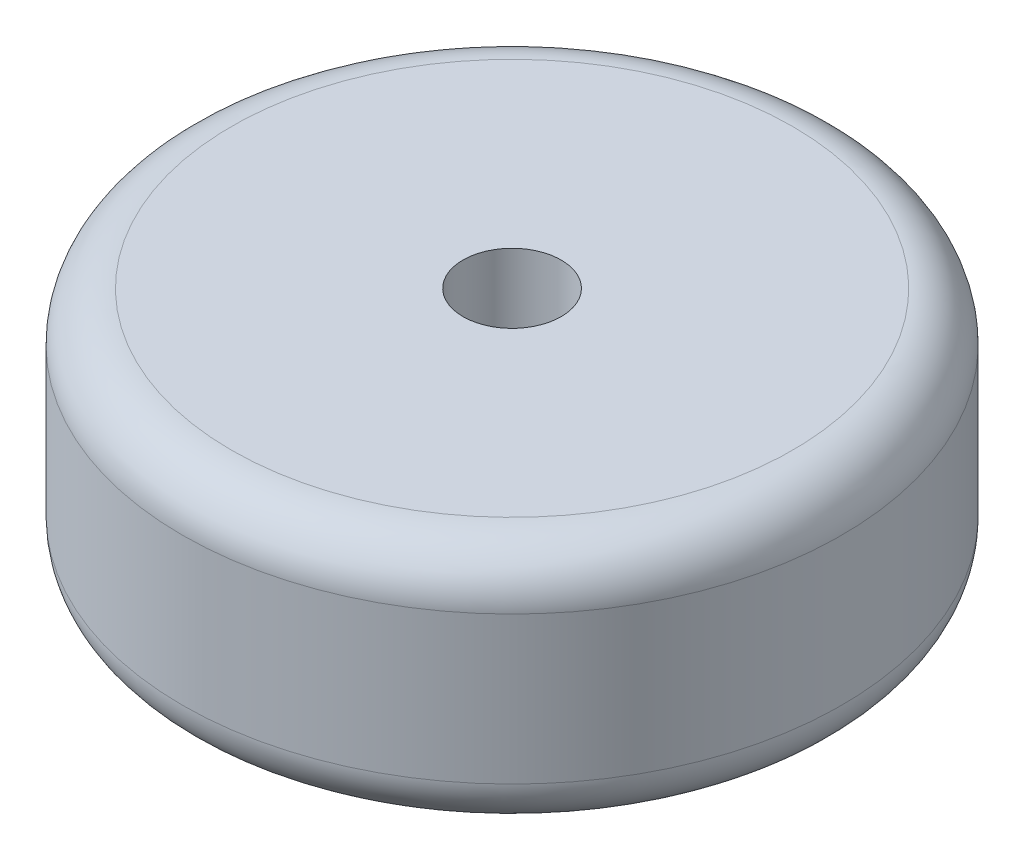
SolidWorks part; units mm, degrees
material "Custom Plastic"
ref_plane "Front Plane" through (0, 0, 0) normal (0, 0, 1) x (1, 0, 0)
ref_plane "Top Plane" through (0, 0, 0) normal (0, 1, 0) x (1, 0, 0)
ref_plane "Right Plane" through (0, 0, 0) normal (1, 0, 0) x (0, 0, -1)
sketch "Sketch1" plane through (0, 0, 0) normal (0, 1, 0) x (1, 0, 0)
  circle A0 centre (0, 0) radius 6.715
  dimension "D1" = 13.43
extrude "Boss-Extrude1" add sketch "Sketch1" along normal blind 5
fillet "Fillet1" radius 1 2 edges at (0, 0, 6.715) (0, 5, 6.715)
sketch "Sketch2" plane through (0, 5, 0) normal (0, 1, 0) x (1, 0, 0)
  circle A0 centre (0, 0) radius 1
  dimension "D1" = 2
extrude "Cut-Extrude1" cut sketch "Sketch2" against normal up to next
